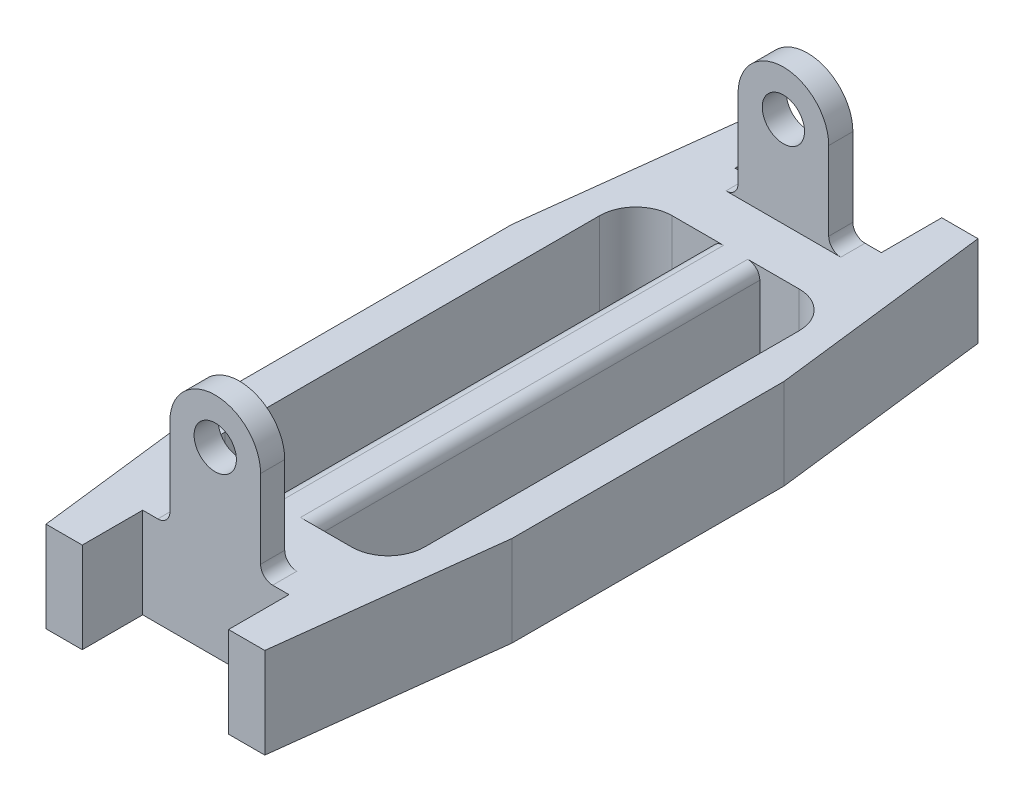
SolidWorks part; units mm, degrees
ref_plane "Front Plane" through (0, 0, 0) normal (0, 0, 1) x (1, 0, 0)
ref_plane "Top Plane" through (0, 0, 0) normal (0, 1, 0) x (1, 0, 0)
ref_plane "Right Plane" through (0, 0, 0) normal (1, 0, 0) x (0, 0, -1)
sketch "Sketch1" plane through (0, 0, 0) normal (0, 1, 0) x (1, 0, 0)
  line L0 (-11.25, -11.25) -> (-11.25, 11.25)
  line L1 (8.25, -8.25) -> (-8.25, -8.25)
  line L2 (8.25, -8.25) -> (8.25, 8.25)
  line L3 (8.25, 8.25) -> (-8.25, 8.25)
  line L4 (-8.25, -8.25) -> (-8.25, 8.25)
  line L8 (11.25, -11.25) -> (11.25, 11.25)
  line L10 (11.25, 11.25) -> (-11.25, 11.25) construction
  line L11 (11.25, -11.25) -> (-11.25, -11.25) construction
  line L12 (-55, 0) -> (55, 0) construction
  line L17 (-9.05, 29.5) -> (-6.05, 29.5)
  line L21 (-6.05, 29.5) -> (-6.05, 24.5)
  line L22 (-6.05, 24.5) -> (6.05, 24.5)
  line L23 (6.05, 24.5) -> (6.05, 29.5)
  line L24 (6.05, 29.5) -> (9.05, 29.5)
  line L28 (-9.05, 29.5) -> (-11.25, 11.25)
  line L29 (9.05, 29.5) -> (11.25, 11.25)
  line L30 (9.05, -29.5) -> (11.25, -11.25)
  line L31 (-9.05, -29.5) -> (-11.25, -11.25)
  line L32 (6.05, -29.5) -> (9.05, -29.5)
  line L33 (6.05, -24.5) -> (6.05, -29.5)
  line L34 (-6.05, -29.5) -> (-6.05, -24.5)
  line L35 (-9.05, -29.5) -> (-6.05, -29.5)
  line L36 (-6.05, -24.5) -> (6.05, -24.5)
  point P0 (0, 8.25)
  dimension "D2" = 5
  dimension "D3" = 12.1
  dimension "D4" = 3
  dimension "D5" = 49
  dimension "D6" = 22.5
  dimension "D1" = 3
extrude "Boss-Extrude2" add sketch "Sketch1" along normal blind 7.5
sketch "Sketch2" plane through (0, 7.5, 0) normal (0, 1, 0) x (1, 0, 0)
  line L0 (8.25, 8.25) -> (-8.25, 8.25) construction
  line L1 (0, 24.5) -> (0, 8.25) construction
  line L2 (6.05, 24.5) -> (-6.05, 24.5) construction
  line L3 (-8.25, 8.25) -> (8.25, 8.25)
  line L4 (-55, 0) -> (55, 0) construction
  line L5 (-8.25, -8.25) -> (8.25, -8.25)
  line L6 (-8.25, 8.25) -> (-8.25, 18.5)
  line L7 (-8.25, 18.5) -> (8.25, 18.5)
  line L8 (8.25, 18.5) -> (8.25, 8.25)
  line L9 (-8.25, -8.25) -> (-8.25, -18.5)
  line L10 (-8.25, -18.5) -> (8.25, -18.5)
  line L11 (8.25, -18.5) -> (8.25, -8.25)
  dimension "D1" = 6
extrude "Cut-Extrude1" cut sketch "Sketch2" against normal through all
sketch "Sketch5" plane through (0, 7.5, 0) normal (0, 1, 0) x (1, 0, 0)
  line L0 (-2, 18.5) -> (2, 18.5)
  line L1 (8.25, 18.5) -> (-8.25, 18.5) construction
  line L2 (2, 18.5) -> (2, -18.5)
  line L3 (-8.25, -18.5) -> (8.25, -18.5) construction
  line L4 (2, -18.5) -> (-2, -18.5)
  line L5 (-2, -18.5) -> (-2, 18.5)
  point P9 (0, 18.5)
  dimension "D1" = 4
extrude "Boss-Extrude4" add sketch "Sketch5" against normal up to surface (7.5 mm away) up to face at (0, 0, 0)
sketch "Sketch4" plane through (0, 0, 24.5) normal (0, 0, 1) x (1, 0, 0)
  line L0 (-3.8, 7.5) -> (3.7, 7.5)
  line L1 (-6.05, 7.5) -> (6.05, 7.5) construction
  line L2 (3.7, 7.5) -> (3.7, 15)
  line L4 (-3.8, 15) -> (-3.8, 7.5)
  arc A0 (3.7, 15) -> (-3.8, 15) centre (-0.05, 15) ccw
  circle A1 centre (-0.05, 15) radius 1.75
  circle A4 centre (-0.05, 15) radius 1.75 construction
  dimension "D1" = 2
extrude "Boss-Extrude3" add sketch "Sketch4" against normal blind 2
mirror "Mirror1" about plane through (0, 0, 0) normal (0, 0, 1) of "Boss-Extrude3"
fillet "Fillet1" radius 3 4 edges at (-8.25, 3.75, 18.5) (8.25, 3.75, 18.5) (8.25, 3.75, -18.5) (-8.25, 3.75, -18.5)
fillet "Fillet2" radius 1 4 edges at (-3.8, 7.5, -23.5) (3.7, 7.5, -23.5) (-3.8, 7.5, 23.5) (3.7, 7.5, 23.5)
fillet "Fillet3" radius 1 4 edges at (2, 0, 0) (-2, 0, 0) (2, 7.5, 0) (-2, 7.5, 0)
